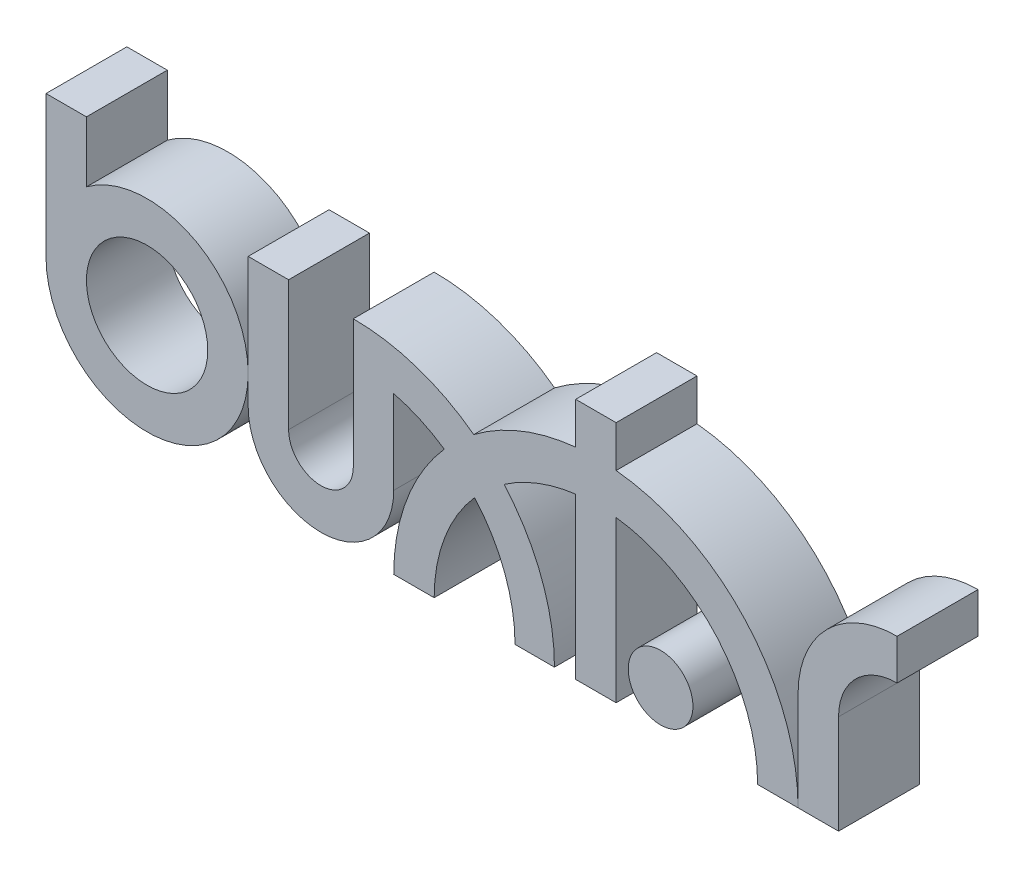
SolidWorks part; units mm, degrees
ref_plane "Спереди" through (0, 0, 0) normal (0, 0, 1) x (1, 0, 0)
ref_plane "Сверху" through (0, 0, 0) normal (0, 1, 0) x (1, 0, 0)
ref_plane "Справа" through (0, 0, 0) normal (1, 0, 0) x (0, 0, -1)
sketch "Эскиз1" plane through (0, 0, 0) normal (0, 0, 1) x (1, 0, 0)
  line L0 (-55.5, 0) -> (-53, 0)
  line L3 (2.5, 30) -> (-2.5, 30)
  line L5 (-25, 0) -> (-20, 0)
  line L6 (-10, 0) -> (-5.1253, 0)
  line L7 (-2.5, 0) -> (-2.5, 19.8431)
  line L8 (2.5, 0) -> (2.5, 19.8431)
  line L9 (-25, 0) -> (-20, 0)
  line L10 (37.25, 24.5) -> (37.25, 19.4951)
  line L11 (20, 0) -> (30.0049, 0)
  line L12 (-2.5, 0) -> (2.5, 0)
  line L13 (-2.5, 24.8747) -> (-2.5, 30)
  line L14 (2.5, 24.8747) -> (2.5, 30)
  line L16 (-25, 8.999) -> (-25, 19.3649)
  line L18 (-30, 8.999) -> (-30, 24.8747)
  line L20 (-38, 8.999) -> (-38, 25.0549)
  line L21 (-38, 25.0549) -> (-43, 25.0549)
  line L22 (-43, 8.999) -> (-43, 25.0549)
  line L23 (25, 0) -> (30.0049, 0)
  line L24 (25, 0) -> (25, 12.25)
  line L26 (30.0049, 0) -> (30.0049, 12.25)
  line L29 (-68, 12.5) -> (-68, 30)
  line L30 (-68, 30) -> (-63, 30)
  line L31 (-63, 22.5) -> (-63, 30)
  arc A2 (20, 0) -> (2.5, 19.8431) centre (0, 0) ccw
  arc A3 (25, 0) -> (2.5, 24.8747) centre (0, 0) ccw
  arc A4 (-2.5, 19.8431) -> (-11.3542, 16.4646) centre (0, 0) ccw
  arc A5 (-2.5, 24.8747) -> (-15.1042, 19.9214) centre (0, 0) ccw
  arc A6 (-10, 0) -> (-15, 13.2288) centre (-30, 0) ccw
  arc A7 (-5.1253, 0) -> (-11.3542, 16.4646) centre (-30, 0) ccw
  circle A8 centre (8, 4.3697) radius 4
  arc A9 (-43, 8.999) -> (-25, 8.999) centre (-34, 8.999) ccw
  arc A10 (-38, 8.999) -> (-30, 8.999) centre (-34, 8.999) ccw
  arc A11 (-18.75, 16.5359) -> (-25, 19.3649) centre (-30, 0) ccw
  arc A12 (-15.1042, 19.9214) -> (-30, 24.8747) centre (-30, 0) ccw
  arc A13 (-18.75, 16.5359) -> (-25, 0) centre (0, 0) ccw
  arc A14 (-15, 13.2288) -> (-20, 0) centre (0, 0) ccw
  arc A15 (37.25, 24.5) -> (25, 12.25) centre (37.25, 12.25) ccw
  arc A16 (37.25, 19.4951) -> (30.0049, 12.25) centre (37.25, 12.25) ccw
  arc A17 (-68, 12.5) -> (-63, 22.5) centre (-55.5, 12.5) ccw
  circle A18 centre (-55.5, 12.5) radius 7.5
extrude "Бобышка-Вытянуть1" add sketch "Эскиз1" along normal blind 10 contours A17 L31 L30 L29 A18 | A14 A6 L6 A7 A4 L7 L12 L8 A2 L11 A3 L14 L3 L13 A5 A12 L18 A10 L20 L21 L22 A9 L16 A11 A13 L5 | A16 L10 A15 L24 L11 L26 | A8
